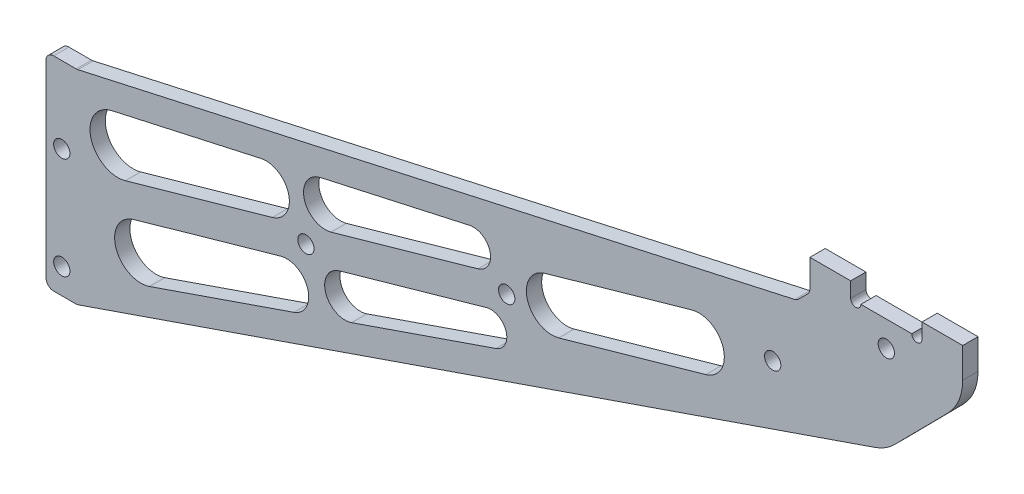
SolidWorks part; units mm, degrees
material "Thornel Mat VMA"
ref_plane "前视基准面" through (0, 0, 0) normal (0, 0, 1) x (1, 0, 0)
ref_plane "上视基准面" through (0, 0, 0) normal (0, 1, 0) x (1, 0, 0)
ref_plane "右视基准面" through (0, 0, 0) normal (1, 0, 0) x (0, 0, -1)
other "Configuration Table"
sketch "草图1" plane through (0, 0, 0) normal (0, 0, 1) x (1, 0, 0)
  line L0 (6.1, 0) -> (150, 32)
  line L1 (150, 32) -> (150, 40)
  line L2 (150, 40) -> (158, 40)
  line L3 (158, 40) -> (158, 37)
  line L4 (158, 37) -> (172, 37)
  line L5 (172, 37) -> (172, 40)
  line L6 (172, 40) -> (180, 40)
  line L7 (180, 40) -> (180, 20)
  line L8 (180, 20) -> (6.1, -40)
  line L10 (6.1, 0) -> (0, 0)
  line L11 (0, 0) -> (0, -40)
  line L12 (0, -40) -> (6.1, -40)
  line L13 (0, -40) -> (0, -46.1927)
  line L14 (0, -46.1927) -> (6.1, -46.1927)
  circle A0 centre (3.1, -35) radius 1.6
  circle A1 centre (3.1, -15) radius 1.6
  circle A2 centre (159, 37) radius 1
  circle A3 centre (171, 37) radius 1
  dimension "D4" = 3.2
  dimension "D14" = 2
  dimension "D1" = 6.1
  dimension "D2" = 20
  dimension "D3" = 3
  dimension "D5" = 40
  dimension "D6" = 15
  dimension "D7" = 180
  dimension "D8" = 8
  dimension "D9" = 3
  dimension "D10" = 30
  dimension "D11" = 80
  dimension "D12" = 5
  dimension "D13" = 20
extrude "凸台-拉伸1" add sketch "草图1" along normal blind 3 contours A3 L4 A2 L3 L2 L1 L0 L10 L11 L12 L8 L7 L6 L5 A1 A0
sketch "草图2" plane through (0, 0, 3) normal (0, 0, 1) x (1, 0, 0)
  line L0 (160, 37) -> (170, 37) construction
  circle A0 centre (165, 32) radius 1.6
  point P4 (165, 37)
  dimension "D1" = 3.2
  dimension "D2" = 5
extrude "切除-拉伸1" cut sketch "草图2" against normal blind 3
chamfer "倒角1" distance 2 angle 45 2 edges at (180, 20, 1.5) (150, 32, 1.5)
sketch "草图3" plane through (0, 0, 3) normal (0, 0, 1) x (1, 0, 0)
  line L0 (6.1, 0) -> (6.1, -40) construction
  line L1 (20.3195, -29.8047) -> (48.6679, -20.0237)
  line L3 (6.1, 0) -> (147.4281, 31.4281) construction
  line L4 (178.1094, 19.3477) -> (6.1, -40) construction
  line L5 (6.1, 0) -> (147.2287, 31.3837) construction
  line L6 (178.1094, 19.3477) -> (6.1, -40) construction
  line L8 (17.2278, -19.9614) -> (46.0776, -11.7767)
  line L11 (99.3276, 6.4488) -> (128.1886, 14.6367) construction
  line L12 (97.9629, 11.259) -> (126.824, 19.4469)
  line L13 (100.6922, 1.6386) -> (129.5533, 9.8265)
  line L14 (60.0073, -16.1114) -> (88.3557, -6.3304)
  line L17 (57.6175, -8.5028) -> (86.4673, -0.3181)
  line L20 (147.2287, 31.3837) -> (332.2333, 72.5244) construction
  line L21 (332.2333, 72.5244) -> (178.1094, 19.3477) construction
  line L22 (332.2333, 72.5244) -> (6.1, -20) construction
  line L23 (15.5902, -14.1892) -> (44.44, -6.0045)
  line L24 (12.9148, -3.6067) -> (42.188, 2.903)
  line L25 (18.6363, -24.9262) -> (14.1, -8.9365) construction
  line L26 (47.2577, -15.9364) -> (43.1857, -1.5832) construction
  line L27 (55.9799, -2.7306) -> (84.8297, 5.4541)
  line L28 (53.8973, 5.5069) -> (83.1706, 12.0166)
  line L29 (58.7062, -12.3404) -> (54.8199, 1.3581) construction
  line L30 (87.3276, -3.3506) -> (83.9056, 8.7114) construction
  arc A4 (97.9629, 11.259) -> (100.6922, 1.6386) centre (99.3276, 6.4488) ccw
  arc A5 (129.5533, 9.8265) -> (126.824, 19.4469) centre (128.1886, 14.6367) ccw
  arc A10 (17.2278, -19.9614) -> (20.3195, -29.8047) centre (18.6363, -24.9262) ccw
  arc A11 (48.6679, -20.0237) -> (46.0776, -11.7767) centre (47.2577, -15.9364) ccw
  arc A14 (57.6175, -8.5028) -> (60.0073, -16.1114) centre (58.7062, -12.3404) ccw
  arc A15 (88.3557, -6.3304) -> (86.4673, -0.3181) centre (87.3276, -3.3506) ccw
  arc A16 (12.9148, -3.6067) -> (15.5902, -14.1892) centre (14.1, -8.9365) ccw
  arc A17 (44.44, -6.0045) -> (42.188, 2.903) centre (43.1857, -1.5832) ccw
  arc A18 (53.8973, 5.5069) -> (55.9799, -2.7306) centre (54.8199, 1.3581) ccw
  arc A19 (84.8297, 5.4541) -> (83.1706, 12.0166) centre (83.9056, 8.7114) ccw
  circle A20 centre (51.031, -7.253) radius 1.6
  circle A21 centre (90.4586, 3.9327) radius 1.6
  circle A22 centre (142.6886, 18.7504) radius 1.6
  point P16 (113.7581, 10.5427)
  dimension "D3" = 3
  dimension "D9" = 5
  dimension "D11" = 3.2
  dimension "D1" = 30
  dimension "D2" = 5
  dimension "D4" = 10
  dimension "D5" = 3
  dimension "D6" = 8
  dimension "D7" = 12
  dimension "D8" = 12
  dimension "D10" = 30
  dimension "D12" = 6
  dimension "D13" = 5
  dimension "D14" = 14.5
extrude "切除-拉伸2" cut sketch "草图3" against normal blind 3
sketch "草图4" plane through (0, 0, 3) normal (0, 0, 1) x (1, 0, 0)
  line L0 (150, 34) -> (165, 32) construction
  line L2 (165, 32) -> (180, 30) construction
  line L3 (180, 40) -> (180, 23.2302) construction
  line L4 (180, 30) -> (165, 14.8246)
  line L5 (178.1094, 19.3477) -> (6.1, -40) construction
  line L6 (178.1094, 19.3477) -> (180, 23.2302) construction
  line L7 (178.1094, 19.3477) -> (165, 14.8246)
  line L8 (178.1094, 19.3477) -> (180, 23.2302)
  line L9 (180, 30) -> (180, 23.2302)
extrude "切除-拉伸3" cut sketch "草图4" against normal blind 3
fillet "圆角1" radius 10 2 edges at (165, 14.8246, 1.5) (180, 30, 1.5)
fillet "圆角2" radius 1.5 6 edges at (0, -40, 1.5) (6.1, -40, 1.5) (6.1, 0, 1.5) (0, 0, 1.5) (147.4281, 31.4281, 1.5) (150, 34, 1.5)
